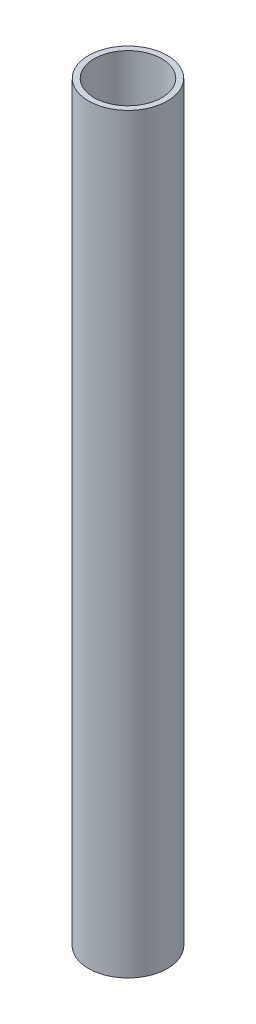
SolidWorks part; units mm, degrees
ref_plane "前视基准面" through (0, 0, 0) normal (0, 0, 1) x (1, 0, 0)
ref_plane "上视基准面" through (0, 0, 0) normal (0, 1, 0) x (1, 0, 0)
ref_plane "右视基准面" through (0, 0, 0) normal (1, 0, 0) x (0, 0, -1)
sketch "草图1" plane through (0, 0, 0) normal (0, 1, 0) x (1, 0, 0)
  circle A0 centre (0, 0) radius 5.25
  dimension "D1" = 10.5
extrude "凸台-拉伸1" add sketch "草图1" along normal mid plane 100
hole_wizard "M10x1.0 螺纹孔1" positions "3D草图1" profile "草图2" tap size "M10x1.0" standard "GB" end condition through all
sketch3d "3D草图1"
  line L0 (0, 50, 0) -> (0, -50, 0) construction
  point P0 (0, 50, 0)
sketch "草图2" plane through (0, 50, 0) normal (1, 0, 0) x (0, 0, 1)
  line L0 (0, 0) -> (0, 100)
  line L1 (0, 100) -> (4.5, 100)
  line L2 (4.5, 100) -> (4.5, 0)
  line L5 (4.5, 0) -> (0, 0)
  line L11 (0, -6.35) -> (0, 107.95) construction
  dimension "通孔螺纹孔钻头直径" = 9
  dimension "通孔螺纹孔钻头深度" = 100
cosmetic thread "孔螺蚊线1" parameters "D2"=10
